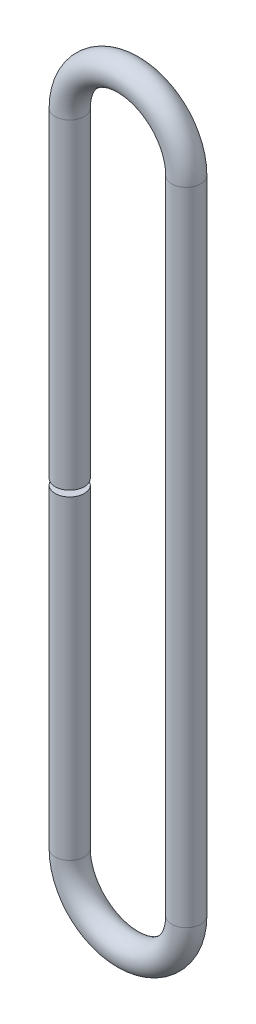
SolidWorks part; units mm, degrees
ref_plane "Front Plane" through (0, 0, 0) normal (0, 0, 1) x (1, 0, 0)
ref_plane "Top Plane" through (0, 0, 0) normal (0, 1, 0) x (1, 0, 0)
ref_plane "Right Plane" through (0, 0, 0) normal (1, 0, 0) x (0, 0, -1)
sketch "Sketch1" plane through (0, 0, 0) normal (0, 0, 1) x (1, 0, 0)
  line L0 (0, 0.1) -> (0, 11.1)
  line L1 (4, 11.1) -> (4, -10.9)
  line L2 (0, -10.9) -> (0, -0.1)
  arc A0 (0, 11.1) -> (4, 11.1) centre (2, 11.1) cw
  arc A1 (4, -10.9) -> (0, -10.9) centre (2, -10.9) cw
  point P8 (0, 0)
  point P10 (0, 0.5)
  point P11 (4, 11.5)
  point P12 (0, 0)
  point P13 (0.5, 0)
  point P14 (0, 0)
  point P15 (0, 0)
  point P16 (0, 0)
  dimension "D1" = 0.1
  dimension "D2" = 0.1
  dimension "D3" = 22
  dimension "D4" = 11
  dimension "D5" = 4
ref_plane "Plane1" through (0, 0.1, 0) normal (0, 1, 0) x (1, 0, 0)
sketch "Sketch2" plane through (0, 0.1, 0) normal (0, 1, 0) x (1, 0, 0)
  circle A0 centre (0, 0) radius 0.5
  dimension "D1" = 1
sweep "Sweep1" add profiles "Sketch2" path "Sketch1"
equation "\"D1@Sketch1\"=\"D2@Sketch1\""
